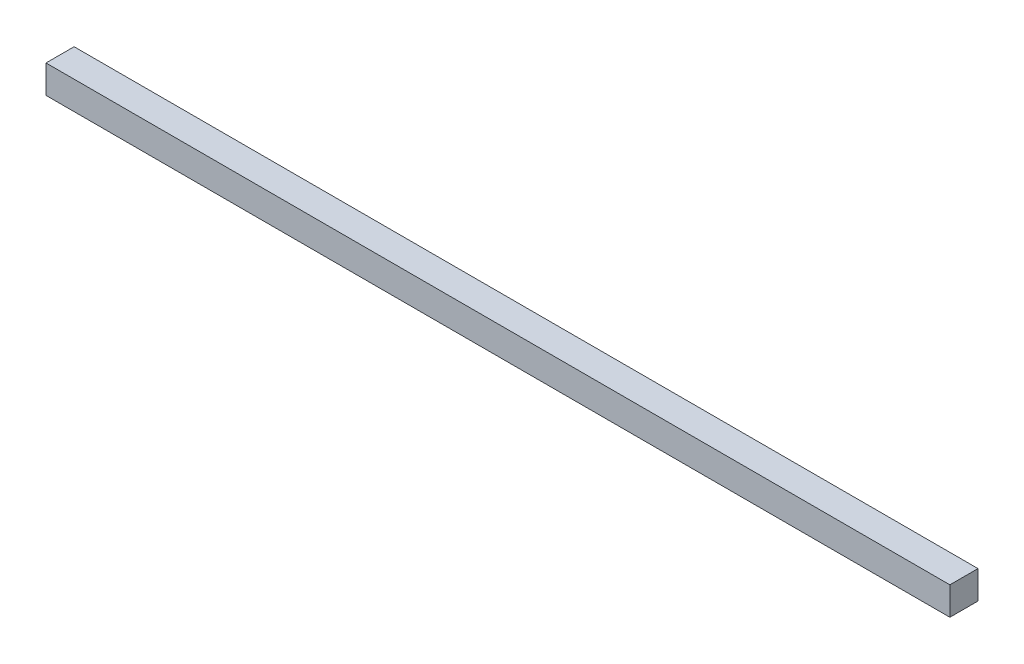
SolidWorks part; units mm, degrees
material "Pine"
ref_plane "Front Plane" through (0, 0, 0) normal (0, 0, 1) x (1, 0, 0)
ref_plane "Top Plane" through (0, 0, 0) normal (0, 1, 0) x (1, 0, 0)
ref_plane "Right Plane" through (0, 0, 0) normal (1, 0, 0) x (0, 0, -1)
sketch "Sketch1" plane through (0, 0, 0) normal (0, 1, 0) x (1, 0, 0)
  line L1 (-306.1398, -9.525) -> (306.1399, -9.525)
  line L2 (-306.1398, -9.525) -> (-306.1398, 9.525)
  line L3 (-306.1398, 9.525) -> (306.1399, 9.525)
  line L4 (306.1399, -9.525) -> (306.1399, 9.525)
  line L5 (-306.1398, -9.525) -> (306.1399, 9.525) construction
  line L6 (-306.1398, 9.525) -> (306.1399, -9.525) construction
  point P0 (0, 0)
  dimension "D1" = 19.05
  dimension "D2" = 612.2797
extrude "Boss-Extrude1" add sketch "Sketch1" along normal blind 19.05
hole_wizard "1/8 (0.125) Diameter Hole1" positions "Sketch2" profile "Sketch3" hole size "1/8" standard "ANSI Inch"
sketch "Sketch2" plane through (0, 0, 0) normal (0, -1, 0) x (-1, 0, 0)
  line L0 (254, 0) -> (152.4, 0) construction
  line L1 (152.4, 0) -> (50.8, 0) construction
  line L2 (50.8, 0) -> (-50.8, 0) construction
  line L3 (-50.8, 0) -> (-152.4, 0) construction
  line L4 (-152.4, 0) -> (-254, 0) construction
  point P0 (254, 0)
  point P2 (152.4, 0)
  point P4 (50.8, 0)
  point P6 (-50.8, 0)
  point P12 (-152.4, 0)
  point P14 (-254, 0)
  point P26 (0, 0)
  point P27 (264.3329, 0)
  dimension "D1" = 101.6
sketch "Sketch3" plane through (-254, 0, 0) normal (1, 0, 0) x (0, 0, -1)
  line L0 (0, 0) -> (0, 12.0664)
  line L1 (0, 12.0664) -> (1.5875, 11.1125)
  line L2 (1.5875, 11.1125) -> (1.5875, 0)
  line L5 (1.5875, 0) -> (0, 0)
  line L10 (0, 12.0664) -> (-1.5875, 11.1125) construction
  line L11 (0, -6.35) -> (0, 107.95) construction
  dimension "Hole Dia." = 3.175
  dimension "Hole Depth" = 11.1125
  dimension "Drill Angle" = 118
